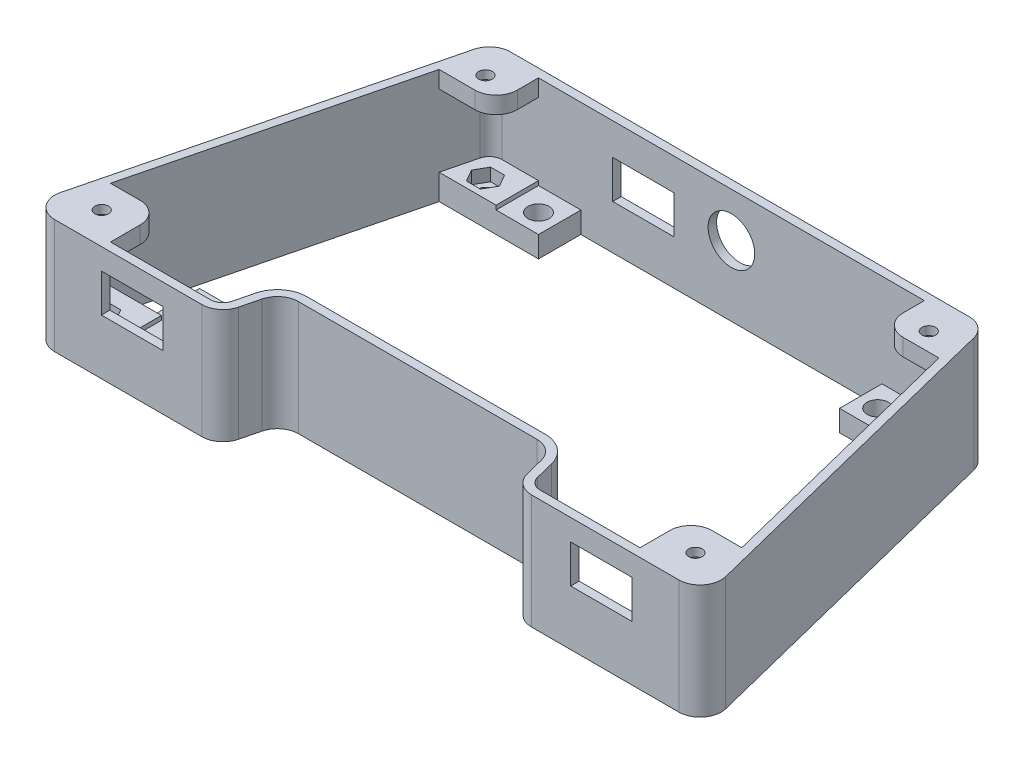
SolidWorks part; units mm, degrees
ref_plane "Ön Düzlem" through (0, 0, 0) normal (0, 0, 1) x (1, 0, 0)
ref_plane "Üst Düzlem" through (0, 0, 0) normal (0, 1, 0) x (1, 0, 0)
ref_plane "Sağ Düzlem" through (0, 0, 0) normal (1, 0, 0) x (0, 0, -1)
sketch "Çizim1" plane through (0, 0, 0) normal (0, 1, 0) x (1, 0, 0)
  line L0 (3.9039, 0) -> (112.0961, 0)
  line L1 (116.9468, -3.7873) -> (136.4468, -81.7873)
  line L2 (131.5961, -88) -> (96.9039, -88)
  line L3 (92.0532, -84.2127) -> (90.9468, -79.7873)
  line L4 (86.0961, -76) -> (29.9039, -76)
  line L5 (25.0532, -79.7873) -> (23.9468, -84.2127)
  line L6 (19.0961, -88) -> (-15.5961, -88)
  line L7 (-20.4468, -81.7873) -> (-0.9468, -3.7873)
  line L8 (58, 0) -> (58, -76) construction
  arc A0 (23.9468, -84.2127) -> (19.0961, -88) centre (19.0961, -83) cw
  arc A1 (96.9039, -88) -> (92.0532, -84.2127) centre (96.9039, -83) cw
  arc A2 (29.9039, -76) -> (25.0532, -79.7873) centre (29.9039, -81) ccw
  arc A3 (90.9468, -79.7873) -> (86.0961, -76) centre (86.0961, -81) ccw
  arc A4 (131.5961, -88) -> (136.4468, -81.7873) centre (131.5961, -83) ccw
  arc A5 (-15.5961, -88) -> (-20.4468, -81.7873) centre (-15.5961, -83) cw
  arc A6 (116.9468, -3.7873) -> (112.0961, 0) centre (112.0961, -5) ccw
  arc A7 (3.9039, 0) -> (-0.9468, -3.7873) centre (3.9039, -5) ccw
  point P18 (23, -88)
  point P21 (93, -88)
  point P28 (138, -88)
  point P31 (-22, -88)
  point P34 (116, 0)
  point P37 (0, 0)
  dimension "D6" = 5
  dimension "D7" = 5
  dimension "D1" = 116
  dimension "D2" = 160
  dimension "D3" = 76
  dimension "D4" = 12
  dimension "D5" = 45
extrude "Yükseklik-Ekstrüzyon1" add sketch "Çizim1" along normal blind 3
sketch "Çizim2" plane through (0, 3, 0) normal (0, 1, 0) x (1, 0, 0)
  line L8 (23.9468, -84.2127) -> (25.0532, -79.7873)
  line L9 (29.9039, -76) -> (86.0961, -76)
  line L10 (90.9468, -79.7873) -> (92.0532, -84.2127)
  line L11 (96.9039, -88) -> (131.5961, -88)
  line L12 (136.4468, -81.7873) -> (116.9468, -3.7873)
  line L13 (112.0961, 0) -> (3.9039, 0)
  line L14 (-0.9468, -3.7873) -> (-20.4468, -81.7873)
  line L15 (-15.5961, -88) -> (19.0961, -88)
  line L16 (23.9468, -84.2127) -> (25.0532, -79.7873)
  line L17 (29.9039, -76) -> (86.0961, -76)
  line L18 (90.9468, -79.7873) -> (92.0532, -84.2127)
  line L19 (96.9039, -88) -> (131.5961, -88)
  line L20 (136.4468, -81.7873) -> (116.9468, -3.7873)
  line L21 (112.0961, 0) -> (3.9039, 0)
  line L22 (-0.9468, -3.7873) -> (-20.4468, -81.7873)
  line L23 (-15.5961, -88) -> (19.0961, -88)
  line L32 (22.0065, -83.7276) -> (23.1129, -79.3023)
  line L33 (29.9039, -74) -> (86.0961, -74)
  line L34 (92.8871, -79.3023) -> (93.9935, -83.7276)
  line L35 (96.9039, -86) -> (131.5961, -86)
  line L36 (134.5065, -82.2724) -> (115.0065, -4.2724)
  line L37 (112.0961, -2) -> (3.9039, -2)
  line L38 (0.9935, -4.2724) -> (-18.5065, -82.2724)
  line L39 (-15.5961, -86) -> (19.0961, -86)
  line L40 (22.0065, -83.7276) -> (23.1129, -79.3023)
  line L41 (29.9039, -74) -> (86.0961, -74)
  line L42 (92.8871, -79.3023) -> (93.9935, -83.7276)
  line L43 (96.9039, -86) -> (131.5961, -86)
  line L44 (134.5065, -82.2724) -> (115.0065, -4.2724)
  line L45 (112.0961, -2) -> (3.9039, -2)
  line L46 (0.9935, -4.2724) -> (-18.5065, -82.2724)
  line L47 (-15.5961, -86) -> (19.0961, -86)
  arc A8 (19.0961, -88) -> (23.9468, -84.2127) centre (19.0961, -83) ccw
  arc A9 (29.9039, -76) -> (25.0532, -79.7873) centre (29.9039, -81) ccw
  arc A10 (90.9468, -79.7873) -> (86.0961, -76) centre (86.0961, -81) ccw
  arc A11 (92.0532, -84.2127) -> (96.9039, -88) centre (96.9039, -83) ccw
  arc A12 (131.5961, -88) -> (136.4468, -81.7873) centre (131.5961, -83) ccw
  arc A13 (116.9468, -3.7873) -> (112.0961, 0) centre (112.0961, -5) ccw
  arc A14 (3.9039, 0) -> (-0.9468, -3.7873) centre (3.9039, -5) ccw
  arc A15 (-20.4468, -81.7873) -> (-15.5961, -88) centre (-15.5961, -83) ccw
  arc A16 (19.0961, -88) -> (23.9468, -84.2127) centre (19.0961, -83) ccw
  arc A17 (29.9039, -76) -> (25.0532, -79.7873) centre (29.9039, -81) ccw
  arc A18 (90.9468, -79.7873) -> (86.0961, -76) centre (86.0961, -81) ccw
  arc A19 (92.0532, -84.2127) -> (96.9039, -88) centre (96.9039, -83) ccw
  arc A20 (131.5961, -88) -> (136.4468, -81.7873) centre (131.5961, -83) ccw
  arc A21 (116.9468, -3.7873) -> (112.0961, 0) centre (112.0961, -5) ccw
  arc A22 (3.9039, 0) -> (-0.9468, -3.7873) centre (3.9039, -5) ccw
  arc A23 (-20.4468, -81.7873) -> (-15.5961, -88) centre (-15.5961, -83) ccw
  arc A32 (19.0961, -86) -> (22.0065, -83.7276) centre (19.0961, -83) ccw
  arc A33 (29.9039, -74) -> (23.1129, -79.3023) centre (29.9039, -81) ccw
  arc A34 (92.8871, -79.3023) -> (86.0961, -74) centre (86.0961, -81) ccw
  arc A35 (93.9935, -83.7276) -> (96.9039, -86) centre (96.9039, -83) ccw
  arc A36 (131.5961, -86) -> (134.5065, -82.2724) centre (131.5961, -83) ccw
  arc A37 (115.0065, -4.2724) -> (112.0961, -2) centre (112.0961, -5) ccw
  arc A38 (3.9039, -2) -> (0.9935, -4.2724) centre (3.9039, -5) ccw
  arc A39 (-18.5065, -82.2724) -> (-15.5961, -86) centre (-15.5961, -83) ccw
  arc A40 (19.0961, -86) -> (22.0065, -83.7276) centre (19.0961, -83) ccw
  arc A41 (29.9039, -74) -> (23.1129, -79.3023) centre (29.9039, -81) ccw
  arc A42 (92.8871, -79.3023) -> (86.0961, -74) centre (86.0961, -81) ccw
  arc A43 (93.9935, -83.7276) -> (96.9039, -86) centre (96.9039, -83) ccw
  arc A44 (131.5961, -86) -> (134.5065, -82.2724) centre (131.5961, -83) ccw
  arc A45 (115.0065, -4.2724) -> (112.0961, -2) centre (112.0961, -5) ccw
  arc A46 (3.9039, -2) -> (0.9935, -4.2724) centre (3.9039, -5) ccw
  arc A47 (-18.5065, -82.2724) -> (-15.5961, -86) centre (-15.5961, -83) ccw
  dimension "D1" = 0
  dimension "D2" = 2
extrude "Yükseklik-Ekstrüzyon2" add sketch "Çizim2" along normal blind 24
sketch "Çizim3" plane through (0, 3, 0) normal (0, 1, 0) x (1, 0, 0)
  line L8 (-15.5961, -86) -> (19.0961, -86)
  line L9 (22.0065, -83.7276) -> (23.1129, -79.3023)
  line L10 (29.9039, -74) -> (86.0961, -74)
  line L11 (92.8871, -79.3023) -> (93.9935, -83.7276)
  line L12 (96.9039, -86) -> (131.5961, -86)
  line L13 (134.5065, -82.2724) -> (115.0065, -4.2724)
  line L14 (112.0961, -2) -> (3.9039, -2)
  line L15 (0.9935, -4.2724) -> (-18.5065, -82.2724)
  line L16 (-15.5961, -86) -> (19.0961, -86)
  line L17 (22.0065, -83.7276) -> (23.1129, -79.3023)
  line L18 (29.9039, -74) -> (86.0961, -74)
  line L19 (92.8871, -79.3023) -> (93.9935, -83.7276)
  line L20 (96.9039, -86) -> (131.5961, -86)
  line L21 (134.5065, -82.2724) -> (115.0065, -4.2724)
  line L22 (112.0961, -2) -> (3.9039, -2)
  line L23 (0.9935, -4.2724) -> (-18.5065, -82.2724)
  arc A8 (19.0961, -86) -> (22.0065, -83.7276) centre (19.0961, -83) ccw
  arc A9 (29.9039, -74) -> (23.1129, -79.3023) centre (29.9039, -81) ccw
  arc A10 (92.8871, -79.3023) -> (86.0961, -74) centre (86.0961, -81) ccw
  arc A11 (93.9935, -83.7276) -> (96.9039, -86) centre (96.9039, -83) ccw
  arc A12 (131.5961, -86) -> (134.5065, -82.2724) centre (131.5961, -83) ccw
  arc A13 (115.0065, -4.2724) -> (112.0961, -2) centre (112.0961, -5) ccw
  arc A14 (3.9039, -2) -> (0.9935, -4.2724) centre (3.9039, -5) ccw
  arc A15 (-18.5065, -82.2724) -> (-15.5961, -86) centre (-15.5961, -83) ccw
  arc A16 (19.0961, -86) -> (22.0065, -83.7276) centre (19.0961, -83) ccw
  arc A17 (29.9039, -74) -> (23.1129, -79.3023) centre (29.9039, -81) ccw
  arc A18 (92.8871, -79.3023) -> (86.0961, -74) centre (86.0961, -81) ccw
  arc A19 (93.9935, -83.7276) -> (96.9039, -86) centre (96.9039, -83) ccw
  arc A20 (131.5961, -86) -> (134.5065, -82.2724) centre (131.5961, -83) ccw
  arc A21 (115.0065, -4.2724) -> (112.0961, -2) centre (112.0961, -5) ccw
  arc A22 (3.9039, -2) -> (0.9935, -4.2724) centre (3.9039, -5) ccw
  arc A23 (-18.5065, -82.2724) -> (-15.5961, -86) centre (-15.5961, -83) ccw
  dimension "D1" = 0
extrude "Kes-Ekstrüzyon1" cut sketch "Çizim3" against normal blind 27
sketch "Çizim4" plane through (0, 0, 0) normal (0, 0, -1) x (-1, 0, 0)
  line L0 (-3.9039, 16.5) -> (-112.0961, 16.5) construction
  line L1 (-3.9039, 27) -> (-3.9039, 0) construction
  line L2 (-112.0961, 27) -> (-112.0961, 0) construction
  line L3 (-112.0961, 0) -> (-3.9039, 0) construction
  line L4 (-58, 16.5) -> (-58, 0) construction
  circle A0 centre (-58, 16.5) radius 5.5
  dimension "D2" = 11
  dimension "D1" = 16.5
extrude "Kes-Ekstrüzyon2" cut sketch "Çizim4" against normal blind 10
sketch "Çizim5" plane through (0, 0, 0) normal (0, 0, -1) x (-1, 0, 0)
  line L0 (-3.9039, 15) -> (-112.0961, 15) construction
  line L1 (-3.9039, 27) -> (-3.9039, 0) construction
  line L2 (-112.0961, 27) -> (-112.0961, 0) construction
  line L3 (-112.0961, 0) -> (-3.9039, 0) construction
  line L4 (-30, 10.5) -> (-44.5, 10.5)
  line L5 (-30, 10.5) -> (-30, 19.5)
  line L6 (-30, 19.5) -> (-44.5, 19.5)
  line L7 (-44.5, 10.5) -> (-44.5, 19.5)
  dimension "D1" = 14.5
  dimension "D2" = 9
  dimension "D3" = 30
  dimension "D4" = 15
extrude "Kes-Ekstrüzyon3" cut sketch "Çizim5" against normal blind 10
sketch "Çizim7" plane through (0, 0, 0) normal (0, -1, 0) x (1, 0, 0)
  line L0 (10.5616, 2) -> (10.5616, 10)
  line L1 (3.9039, 2) -> (112.0961, 2) construction
  line L2 (6.5616, 14) -> (-1.4384, 14)
  line L3 (-18.5065, 82.2724) -> (0.9935, 4.2724) construction
  line L4 (-1.4384, 14) -> (0.9935, 4.2724)
  line L5 (3.9039, 2) -> (10.5616, 2)
  line L6 (58, 2) -> (58, 74) construction
  line L7 (86.0961, 74) -> (29.9039, 74) construction
  line L8 (112.0961, 2) -> (105.4384, 2)
  line L9 (117.4384, 14) -> (115.0065, 4.2724)
  line L10 (109.4384, 14) -> (117.4384, 14)
  line L11 (105.4384, 2) -> (105.4384, 10)
  line L12 (113.9424, 2.6354) -> (106.61, 12.8284) construction
  line L13 (2.0576, 2.6354) -> (9.39, 12.8284) construction
  arc A0 (0.9935, 4.2724) -> (3.9039, 2) centre (3.9039, 5) ccw construction
  arc A1 (0.9935, 4.2724) -> (3.9039, 2) centre (3.9039, 5) ccw
  arc A2 (6.5616, 14) -> (10.5616, 10) centre (6.5616, 10) cw
  arc A3 (109.4384, 14) -> (105.4384, 10) centre (109.4384, 10) ccw
  arc A4 (115.0065, 4.2724) -> (112.0961, 2) centre (112.0961, 5) cw
  circle A5 centre (110.2762, 7.7319) radius 1.65
  circle A6 centre (5.7238, 7.7319) radius 1.65
  point P10 (10.5616, 14)
  point P22 (105.4384, 14)
  dimension "D3" = 4
  dimension "D4" = 3.3
  dimension "D5" = 3.3
  dimension "D1" = 12
  dimension "D2" = 12
extrude "Yükseklik-Ekstrüzyon3" add sketch "Çizim7" against normal blind 2
sketch "Çizim8" plane through (0, 0, 0) normal (0, -1, 0) x (1, 0, 0)
  line L0 (132.4384, 74) -> (124.4384, 74)
  line L1 (117.4384, 14) -> (134.5065, 82.2724) construction
  line L2 (120.4384, 78) -> (120.4384, 86)
  line L3 (131.5961, 86) -> (96.9039, 86) construction
  line L4 (131.5961, 86) -> (120.4384, 86)
  line L5 (132.4384, 74) -> (134.5065, 82.2724)
  line L6 (58, 74) -> (58, 39.038) construction
  line L7 (-16.4384, 74) -> (-18.5065, 82.2724)
  line L8 (124.4384, 78) -> (131.5961, 83) construction
  line L9 (-15.5961, 86) -> (-4.4384, 86)
  line L10 (-4.4384, 78) -> (-4.4384, 86)
  line L11 (-16.4384, 74) -> (-8.4384, 74)
  line L13 (29.9039, 74) -> (86.0961, 74) construction
  arc A0 (134.5065, 82.2724) -> (131.5961, 86) centre (131.5961, 83) ccw construction
  arc A1 (134.5065, 82.2724) -> (131.5961, 86) centre (131.5961, 83) ccw
  arc A2 (120.4384, 78) -> (124.4384, 74) centre (124.4384, 78) ccw
  circle A3 centre (128.0173, 80.5) radius 1.65
  circle A4 centre (-12.0173, 80.5) radius 1.65
  arc A5 (-4.4384, 78) -> (-8.4384, 74) centre (-8.4384, 78) cw
  arc A6 (-18.5065, 82.2724) -> (-15.5961, 86) centre (-15.5961, 83) cw
  point P10 (120.4384, 74)
  point P27 (-4.4384, 74)
  dimension "D3" = 4
  dimension "D4" = 3.3
  dimension "D1" = 12
  dimension "D2" = 12
extrude "Yükseklik-Ekstrüzyon4" add sketch "Çizim8" against normal blind 2
sketch "Çizim12" plane through (0, 2, 0) normal (0, 1, 0) x (1, 0, 0)
  line L0 (112.0961, 0) -> (3.9039, 0) construction
  line L1 (7.4559, -4.7319) -> (3.9918, -4.7319)
  line L2 (3.9918, -4.7319) -> (2.2597, -7.7319)
  line L3 (2.2597, -7.7319) -> (3.9918, -10.7319)
  line L4 (3.9918, -10.7319) -> (7.4559, -10.7319)
  line L5 (7.4559, -10.7319) -> (9.1879, -7.7319)
  line L6 (9.1879, -7.7319) -> (7.4559, -4.7319)
  line L7 (-15.5961, -88) -> (19.0961, -88) construction
  line L8 (-8.5532, -80.5) -> (-10.2852, -77.5)
  line L9 (-10.2852, -77.5) -> (-13.7493, -77.5)
  line L10 (-13.7493, -77.5) -> (-15.4814, -80.5)
  line L11 (-15.4814, -80.5) -> (-13.7493, -83.5)
  line L12 (-13.7493, -83.5) -> (-10.2852, -83.5)
  line L13 (-10.2852, -83.5) -> (-8.5532, -80.5)
  line L14 (58, -2) -> (58, -74) construction
  line L15 (112.0961, -2) -> (3.9039, -2) construction
  line L16 (29.9039, -74) -> (86.0961, -74) construction
  line L17 (126.2852, -83.5) -> (124.5532, -80.5)
  line L18 (129.7493, -83.5) -> (126.2852, -83.5)
  line L19 (131.4814, -80.5) -> (129.7493, -83.5)
  line L20 (129.7493, -77.5) -> (131.4814, -80.5)
  line L21 (126.2852, -77.5) -> (129.7493, -77.5)
  line L22 (124.5532, -80.5) -> (126.2852, -77.5)
  line L23 (106.8121, -7.7319) -> (108.5441, -4.7319)
  line L24 (108.5441, -10.7319) -> (106.8121, -7.7319)
  line L25 (112.0082, -10.7319) -> (108.5441, -10.7319)
  line L26 (113.7403, -7.7319) -> (112.0082, -10.7319)
  line L27 (112.0082, -4.7319) -> (113.7403, -7.7319)
  line L28 (108.5441, -4.7319) -> (112.0082, -4.7319)
  circle A0 centre (5.7238, -7.7319) radius 3 construction
  circle A1 centre (-12.0173, -80.5) radius 3 construction
  circle A2 centre (128.0173, -80.5) radius 3 construction
  circle A3 centre (110.2762, -7.7319) radius 3 construction
  dimension "D1" = 6
  dimension "D2" = 6
extrude "Kes-Ekstrüzyon5" cut sketch "Çizim12" against normal blind 10
sketch "Çizim13" plane through (0, 0, 88) normal (0, 0, 1) x (1, 0, 0)
  line L0 (-15.5961, 17.5) -> (136.5961, 17.5) construction
  line L1 (-15.5961, 27) -> (-15.5961, 0) construction
  line L2 (136.5961, 0) -> (136.5961, 27) construction
  line L3 (60.5, 17.5) -> (60.5, 0) construction
  line L4 (-4.5961, 22) -> (9.9039, 22)
  line L5 (-4.5961, 22) -> (-4.5961, 13)
  line L6 (-4.5961, 13) -> (9.9039, 13)
  line L7 (9.9039, 22) -> (9.9039, 13)
  line L8 (29.9039, 0) -> (86.0961, 0) construction
  line L9 (106.0939, 22) -> (106.0939, 13)
  line L10 (120.5939, 13) -> (106.0939, 13)
  line L11 (120.5939, 22) -> (120.5939, 13)
  line L12 (120.5939, 22) -> (106.0939, 22)
  line L13 (96.9039, 27) -> (96.9039, 0) construction
  point P25 (96.9039, 13.5)
  dimension "D1" = 9
  dimension "D2" = 14.5
  dimension "D3" = 5
  dimension "D4" = 11
  dimension "D5" = 14.5
  dimension "D6" = 9
  dimension "D7" = 9.19
extrude "Kes-Ekstrüzyon6" cut sketch "Çizim13" against normal blind 10
sketch "Çizim14" plane through (0, 2, 0) normal (0, 1, 0) x (1, 0, 0)
  line L0 (10.5616, -6) -> (105.4384, -6) construction
  line L1 (10.5616, -2) -> (10.5616, -10) construction
  line L2 (105.4384, -10) -> (105.4384, -2) construction
  line L3 (6.5616, -14) -> (12.5, -14)
  line L4 (12.5, -14) -> (12.5, -2)
  line L5 (112.0961, -2) -> (3.9039, -2) construction
  line L6 (12.5, -2) -> (10.5616, -2)
  line L7 (10.5616, -2) -> (3.9039, -2)
  line L8 (0.9935, -4.2724) -> (-1.4384, -14)
  line L9 (-1.4384, -14) -> (6.5616, -14)
  line L10 (10.5616, -10) -> (10.5616, -2)
  line L14 (10.5616, -10) -> (10.5616, -2)
  line L15 (109.4384, -14) -> (103.5, -14)
  line L16 (103.5, -14) -> (103.5, -2)
  line L17 (103.5, -2) -> (105.4384, -2)
  line L18 (58, -6) -> (58, -2) construction
  line L22 (112.0961, -2) -> (105.4384, -2)
  line L23 (105.4384, -2) -> (105.4384, -10)
  line L24 (109.4384, -14) -> (117.4384, -14)
  line L25 (117.4384, -14) -> (115.0065, -4.2724)
  line L27 (105.4384, -2) -> (105.4384, -10)
  arc A2 (3.9039, -2) -> (0.9935, -4.2724) centre (3.9039, -5) ccw
  arc A3 (6.5616, -14) -> (10.5616, -10) centre (6.5616, -10) ccw
  arc A5 (6.5616, -14) -> (10.5616, -10) centre (6.5616, -10) ccw
  arc A6 (115.0065, -4.2724) -> (112.0961, -2) centre (112.0961, -5) ccw
  arc A7 (105.4384, -10) -> (109.4384, -14) centre (109.4384, -10) ccw
  arc A9 (105.4384, -10) -> (109.4384, -14) centre (109.4384, -10) ccw
  dimension "D3" = 91
  dimension "D1" = 0
  dimension "D2" = 0
extrude "Yükseklik-Ekstrüzyon5" add sketch "Çizim14" against normal up to vertex (2 mm away)
sketch "Çizim15" plane through (0, 2, 0) normal (0, 1, 0) x (1, 0, 0)
  line L0 (12.5, -7.5) -> (103.5, -7.5) construction
  line L1 (12.5, -14) -> (12.5, -2) construction
  line L2 (103.5, -2) -> (103.5, -14) construction
  line L3 (112.0961, -2) -> (3.9039, -2) construction
  line L4 (58, -7.5) -> (58, -24.859) construction
  line L6 (12.5, -14) -> (22.5, -14)
  line L7 (12.5, -14) -> (12.5, -2)
  line L8 (12.5, -2) -> (22.5, -2)
  line L9 (22.5, -14) -> (22.5, -2)
  line L10 (93.5, -2) -> (103.5, -2)
  line L11 (93.5, -2) -> (93.5, -14)
  line L12 (93.5, -14) -> (103.5, -14)
  line L13 (103.5, -2) -> (103.5, -14)
  circle A0 centre (18, -7.5) radius 1.6
  circle A1 centre (98, -7.5) radius 1.6
  dimension "D2" = 3.2
  dimension "D3" = 80
  dimension "D1" = 5.5
  dimension "D4" = 10
extrude "Yükseklik-Ekstrüzyon6" add sketch "Çizim15" along normal blind 3 and the other way blind 2
sketch "Çizim16" plane through (0, 2, 0) normal (0, 1, 0) x (1, 0, 0)
  line L4 (12.5, -2) -> (3.9039, -2)
  line L5 (0.9935, -4.2724) -> (-1.4384, -14)
  line L6 (-1.4384, -14) -> (12.5, -14)
  line L7 (12.5, -14) -> (12.5, -2)
  line L8 (12.5, -2) -> (3.9039, -2)
  line L9 (0.9935, -4.2724) -> (-1.4384, -14)
  line L10 (-1.4384, -14) -> (12.5, -14)
  line L11 (12.5, -14) -> (12.5, -2)
  line L12 (112.0961, -2) -> (103.5, -2)
  line L13 (103.5, -2) -> (103.5, -14)
  line L14 (103.5, -14) -> (117.4384, -14)
  line L15 (117.4384, -14) -> (115.0065, -4.2724)
  line L16 (112.0961, -2) -> (103.5, -2)
  line L17 (103.5, -2) -> (103.5, -14)
  line L18 (103.5, -14) -> (117.4384, -14)
  line L19 (117.4384, -14) -> (115.0065, -4.2724)
  arc A1 (3.9039, -2) -> (0.9935, -4.2724) centre (3.9039, -5) ccw
  arc A2 (3.9039, -2) -> (0.9935, -4.2724) centre (3.9039, -5) ccw
  arc A3 (115.0065, -4.2724) -> (112.0961, -2) centre (112.0961, -5) ccw
  arc A4 (115.0065, -4.2724) -> (112.0961, -2) centre (112.0961, -5) ccw
  dimension "D1" = 0
  dimension "D2" = 0
extrude "Yükseklik-Ekstrüzyon7" add sketch "Çizim16" along normal blind 4
sketch "Çizim17" plane through (0, 0, 0) normal (0, -1, 0) x (1, 0, 0)
  line L0 (112.0082, 4.7319) -> (113.7403, 7.7319) construction
  line L1 (112.0082, 4.7319) -> (113.7403, 7.7319)
  line L2 (113.7403, 7.7319) -> (112.0082, 10.7319)
  line L3 (112.0082, 10.7319) -> (108.5441, 10.7319)
  line L4 (108.5441, 10.7319) -> (106.8121, 7.7319)
  line L5 (106.8121, 7.7319) -> (108.5441, 4.7319)
  line L6 (108.5441, 4.7319) -> (112.0082, 4.7319)
  line L7 (108.5441, 4.7319) -> (112.0082, 4.7319) construction
  line L8 (112.0082, 10.7319) -> (108.5441, 10.7319) construction
  line L9 (3.9918, 4.7319) -> (7.4559, 4.7319) construction
  line L10 (7.4559, 4.7319) -> (9.1879, 7.7319)
  line L11 (9.1879, 7.7319) -> (7.4559, 10.7319)
  line L12 (7.4559, 10.7319) -> (3.9918, 10.7319)
  line L13 (3.9918, 10.7319) -> (2.2597, 7.7319)
  line L14 (2.2597, 7.7319) -> (3.9918, 4.7319)
  line L15 (3.9918, 4.7319) -> (7.4559, 4.7319)
  line L16 (9.1879, 7.7319) -> (7.4559, 4.7319) construction
  circle A0 centre (110.2762, 7.7319) radius 3 construction
  circle A1 centre (110.2762, 7.7319) radius 1.6
  circle A2 centre (5.7238, 7.7319) radius 1.6
  circle A3 centre (5.7238, 7.7319) radius 3 construction
  dimension "D1" = 3.2
  dimension "D2" = 6
  dimension "D3" = 3.2
extrude "Yükseklik-Ekstrüzyon8" add sketch "Çizim17" against normal blind 3
sketch "Çizim18" plane through (0, 2, 0) normal (0, -1, 0) x (1, 0, 0)
  circle A1 centre (110.2762, 7.7319) radius 1.6
  circle A2 centre (110.2762, 7.7319) radius 1.6
  circle A3 centre (5.7238, 7.7319) radius 1.6
  circle A4 centre (5.7238, 7.7319) radius 1.6
  dimension "D1" = 0
  dimension "D2" = 0
extrude "Kes-Ekstrüzyon7" cut sketch "Çizim18" against normal blind 3
sketch "Çizim19" plane through (0, 6, 0) normal (0, 1, 0) x (1, 0, 0)
  line L0 (-1.4384, -14) -> (12.5, -14) construction
  line L1 (7.3693, -4.8819) -> (4.0784, -4.8819)
  line L2 (4.0784, -4.8819) -> (2.4329, -7.7319)
  line L3 (2.4329, -7.7319) -> (4.0784, -10.5819)
  line L4 (4.0784, -10.5819) -> (7.3693, -10.5819)
  line L5 (7.3693, -10.5819) -> (9.0147, -7.7319)
  line L6 (9.0147, -7.7319) -> (7.3693, -4.8819)
  line L7 (103.5, -14) -> (117.4384, -14) construction
  line L8 (106.9853, -7.7319) -> (108.6307, -10.5819)
  line L9 (108.6307, -10.5819) -> (111.9216, -10.5819)
  line L10 (111.9216, -10.5819) -> (113.5671, -7.7319)
  line L11 (113.5671, -7.7319) -> (111.9216, -4.8819)
  line L12 (111.9216, -4.8819) -> (108.6307, -4.8819)
  line L13 (108.6307, -4.8819) -> (106.9853, -7.7319)
  circle A0 centre (5.7238, -7.7319) radius 2.85 construction
  circle A1 centre (110.2762, -7.7319) radius 2.85 construction
  dimension "D1" = 5.7
  dimension "D2" = 5.7
extrude "Kes-Ekstrüzyon8" cut sketch "Çizim19" against normal blind 3
sketch "Çizim20" plane through (0, 6, 0) normal (0, 1, 0) x (1, 0, 0)
  line L0 (0.9935, -4.2724) -> (-1.4384, -14) construction
  line L1 (-1.4384, -14) -> (117.4384, -14)
  line L3 (-0.9384, -12) -> (116.9384, -12)
  line L5 (-0.9384, -12) -> (-1.4384, -14)
  line L6 (134.5065, -82.2724) -> (115.0065, -4.2724) construction
  line L7 (134.5065, -82.2724) -> (116.9384, -12)
  line M9 (12.5, -14) -> (12.5, -2)
  line M12 (0.9935, -4.2724) -> (-1.4384, -14)
  line M13 (-1.4384, -14) -> (12.5, -14)
  dimension "D1" = 2
extrude "Kes-Ekstrüzyon9" cut sketch "Çizim20" against normal blind 10 contours L3 M12 M13 M9 | L1 L7 L3 M9
sketch "Çizim21" plane through (0, 5, 0) normal (0, 1, 0) x (1, 0, 0)
  circle A0 centre (18, -7.5) radius 2.5
  circle A1 centre (98, -7.5) radius 2.5
  dimension "D1" = 5
  dimension "D2" = 5
extrude "Kes-Ekstrüzyon10" cut sketch "Çizim21" against normal blind 10
sketch "Çizim22" plane through (0, 2, 0) normal (0, 1, 0) x (1, 0, 0)
  line L0 (-15.5961, -86) -> (19.0961, -86) construction
  line L1 (5.5616, -86) -> (-4.4384, -86)
  line L2 (5.5616, -86) -> (5.5616, -66)
  line L3 (5.5616, -66) -> (-4.4384, -66)
  line L4 (-4.4384, -86) -> (-4.4384, -78)
  line L5 (-4.4384, -78) -> (-4.4384, -86) construction
  line L6 (-8.4384, -74) -> (-4.4384, -74)
  line L7 (-4.4384, -74) -> (-4.4384, -66)
  line L8 (-16.4384, -74) -> (-8.4384, -74) construction
  line L9 (96.9039, -86) -> (131.5961, -86) construction
  line L10 (110.4384, -86) -> (120.4384, -86)
  line L11 (110.4384, -86) -> (110.4384, -66)
  line L12 (110.4384, -66) -> (120.4384, -66)
  line L13 (120.4384, -86) -> (120.4384, -78)
  line L14 (120.4384, -86) -> (120.4384, -78) construction
  line L15 (124.4384, -74) -> (120.4384, -74)
  line L16 (120.4384, -74) -> (120.4384, -66)
  arc A0 (-4.4384, -78) -> (-8.4384, -74) centre (-8.4384, -78) ccw construction
  arc A1 (-4.4384, -78) -> (-8.4384, -74) centre (-8.4384, -78) ccw
  arc A2 (124.4384, -74) -> (120.4384, -78) centre (124.4384, -78) ccw construction
  arc A3 (124.4384, -74) -> (120.4384, -78) centre (124.4384, -78) ccw
  dimension "D1" = 20
  dimension "D2" = 10
  dimension "D3" = 10
  dimension "D4" = 20
extrude "Yükseklik-Ekstrüzyon9" add sketch "Çizim22" against normal up to vertex (2 mm away)
sketch "Çizim23" plane through (0, 2, 0) normal (0, 1, 0) x (1, 0, 0)
  line L0 (120.4384, -74) -> (120.4384, -86)
  line L1 (-4.4384, -74) -> (-4.4384, -86)
  line L6 (132.4384, -74) -> (120.4384, -74)
  line L7 (120.4384, -74) -> (120.4384, -66)
  line L8 (120.4384, -66) -> (110.4384, -66)
  line L9 (110.4384, -66) -> (110.4384, -86)
  line L10 (110.4384, -86) -> (131.5961, -86)
  line L11 (134.5065, -82.2724) -> (132.4384, -74)
  line L12 (132.4384, -74) -> (120.4384, -74)
  line L14 (-15.5961, -86) -> (5.5616, -86)
  line L15 (5.5616, -86) -> (5.5616, -66)
  line L16 (120.4384, -86) -> (131.5961, -86)
  line L17 (134.5065, -82.2724) -> (132.4384, -74)
  line L18 (5.5616, -66) -> (-4.4384, -66)
  line L19 (-4.4384, -66) -> (-4.4384, -74)
  line L20 (-4.4384, -74) -> (-16.4384, -74)
  line L21 (-16.4384, -74) -> (-18.5065, -82.2724)
  line L22 (-15.5961, -86) -> (-4.4384, -86)
  line L25 (-4.4384, -66) -> (-4.4384, -74)
  line L26 (-4.4384, -74) -> (-16.4384, -74)
  line L27 (-16.4384, -74) -> (-18.5065, -82.2724)
  arc A1 (131.5961, -86) -> (134.5065, -82.2724) centre (131.5961, -83) ccw
  arc A2 (131.5961, -86) -> (134.5065, -82.2724) centre (131.5961, -83) ccw
  arc A3 (-18.5065, -82.2724) -> (-15.5961, -86) centre (-15.5961, -83) ccw
  arc A4 (-18.5065, -82.2724) -> (-15.5961, -86) centre (-15.5961, -83) ccw
  line M15 (132.4384, -74) -> (120.4384, -74)
  line M19 (110.4384, -86) -> (131.5961, -86)
  arc M20 (131.5961, -86) -> (134.5065, -82.2724) centre (131.5961, -83) ccw
  line M21 (134.5065, -82.2724) -> (132.4384, -74)
  line M22 (131.4814, -80.5) -> (129.7493, -83.5)
  line M23 (129.7493, -83.5) -> (126.2852, -83.5)
  line M24 (126.2852, -83.5) -> (124.5532, -80.5)
  line M25 (124.5532, -80.5) -> (126.2852, -77.5)
  line M26 (126.2852, -77.5) -> (129.7493, -77.5)
  line M27 (129.7493, -77.5) -> (131.4814, -80.5)
  dimension "D1" = 0
  dimension "D2" = 0
extrude "Yükseklik-Ekstrüzyon10" add sketch "Çizim23" along normal blind 4 contours L27 A4 L22 L1 L26 | L0 M15 M19 M20 M21 M27 M22 M23 M24 M25 M26 | M22 M27 M26 M25 M24 M23
sketch "Çizim24" plane through (0, 2, 0) normal (0, -1, 0) x (1, 0, 0)
  line L0 (126.2852, 77.5) -> (129.7493, 77.5) construction
  line L1 (129.7493, 77.5) -> (131.4814, 80.5)
  line L2 (131.4814, 80.5) -> (129.7493, 83.5)
  line L3 (129.7493, 83.5) -> (126.2852, 83.5)
  line L4 (126.2852, 83.5) -> (124.5532, 80.5)
  line L5 (124.5532, 80.5) -> (126.2852, 77.5)
  line L6 (126.2852, 77.5) -> (129.7493, 77.5)
  line L7 (129.7493, 77.5) -> (131.4814, 80.5) construction
  line L8 (124.5532, 80.5) -> (126.2852, 83.5) construction
  line L9 (-10.2852, 77.5) -> (-13.7493, 77.5) construction
  line L10 (-10.2852, 77.5) -> (-8.5532, 80.5)
  line L11 (-8.5532, 80.5) -> (-10.2852, 83.5)
  line L12 (-10.2852, 83.5) -> (-13.7493, 83.5)
  line L13 (-13.7493, 83.5) -> (-15.4814, 80.5)
  line L14 (-15.4814, 80.5) -> (-13.7493, 77.5)
  line L15 (-13.7493, 77.5) -> (-10.2852, 77.5)
  line L16 (-10.2852, 77.5) -> (-8.5532, 80.5) construction
  line L17 (-15.4814, 80.5) -> (-13.7493, 83.5) construction
  circle A0 centre (128.0173, 80.5) radius 3 construction
  circle A1 centre (128.0173, 80.5) radius 1.6
  circle A2 centre (-12.0173, 80.5) radius 1.6
  circle A3 centre (-12.0173, 80.5) radius 3 construction
  dimension "D1" = 3.2
  dimension "D2" = 3.2
extrude "Yükseklik-Ekstrüzyon11" add sketch "Çizim24" along normal blind 2
sketch "Çizim25" plane through (0, 2, 0) normal (0, -1, 0) x (1, 0, 0)
  circle A1 centre (128.0173, 80.5) radius 1.6
  circle A2 centre (128.0173, 80.5) radius 1.6
  circle A3 centre (-12.0173, 80.5) radius 1.6
  circle A4 centre (-12.0173, 80.5) radius 1.6
  dimension "D1" = 0
  dimension "D2" = 0
extrude "Kes-Ekstrüzyon12" cut sketch "Çizim25" against normal blind 10
sketch "Çizim26" plane through (0, 6, 0) normal (0, 1, 0) x (1, 0, 0)
  line L0 (-15.5961, -86) -> (-4.4384, -86) construction
  line L1 (-10.3718, -77.65) -> (-13.6627, -77.65)
  line L2 (-13.6627, -77.65) -> (-15.3082, -80.5)
  line L3 (-15.3082, -80.5) -> (-13.6627, -83.35)
  line L4 (-13.6627, -83.35) -> (-10.3718, -83.35)
  line L5 (-10.3718, -83.35) -> (-8.7264, -80.5)
  line L6 (-8.7264, -80.5) -> (-10.3718, -77.65)
  line L7 (132.4384, -74) -> (120.4384, -74) construction
  line L8 (129.6627, -77.65) -> (126.3718, -77.65)
  line L9 (126.3718, -77.65) -> (124.7264, -80.5)
  line L10 (124.7264, -80.5) -> (126.3718, -83.35)
  line L11 (126.3718, -83.35) -> (129.6627, -83.35)
  line L12 (129.6627, -83.35) -> (131.3082, -80.5)
  line L13 (131.3082, -80.5) -> (129.6627, -77.65)
  circle A0 centre (-12.0173, -80.5) radius 2.85 construction
  circle A1 centre (128.0173, -80.5) radius 2.85 construction
  dimension "D1" = 5.7
  dimension "D2" = 5.7
extrude "Kes-Ekstrüzyon13" cut sketch "Çizim26" against normal up to vertex (3 mm away)
sketch "Çizim27" plane through (0, 2, 0) normal (0, 1, 0) x (1, 0, 0)
  line L5 (-4.4384, -74) -> (-4.4384, -86)
  line L6 (-4.4384, -86) -> (5.5616, -86)
  line L7 (5.5616, -86) -> (5.5616, -66)
  line L8 (5.5616, -66) -> (-4.4384, -66)
  line L9 (-4.4384, -66) -> (-4.4384, -74)
  line L10 (-4.4384, -74) -> (-4.4384, -86)
  line L11 (-4.4384, -86) -> (5.5616, -86)
  line L12 (5.5616, -86) -> (5.5616, -66)
  line L13 (5.5616, -66) -> (-4.4384, -66)
  line L14 (-4.4384, -66) -> (-4.4384, -74)
  line L15 (120.4384, -86) -> (120.4384, -74)
  line L16 (120.4384, -74) -> (120.4384, -66)
  line L17 (120.4384, -66) -> (110.4384, -66)
  line L18 (110.4384, -66) -> (110.4384, -86)
  line L19 (110.4384, -86) -> (120.4384, -86)
  line L20 (120.4384, -86) -> (120.4384, -74)
  line L21 (120.4384, -74) -> (120.4384, -66)
  line L22 (120.4384, -66) -> (110.4384, -66)
  line L23 (110.4384, -66) -> (110.4384, -86)
  line L24 (110.4384, -86) -> (120.4384, -86)
  dimension "D1" = 0
  dimension "D2" = 0
extrude "Yükseklik-Ekstrüzyon12" add sketch "Çizim27" along normal blind 3
sketch "Çizim28" plane through (0, 5, 0) normal (0, 1, 0) x (1, 0, 0)
  line L0 (-4.4384, -74) -> (-16.4384, -74) construction
  line L1 (-4.4384, -66) -> (-6.4384, -66)
  line L2 (-4.4384, -66) -> (-4.4384, -74)
  line L3 (-4.4384, -74) -> (-6.4384, -74)
  line L4 (-6.4384, -66) -> (-6.4384, -74)
  line L5 (132.4384, -74) -> (120.4384, -74) construction
  line L6 (120.4384, -66) -> (122.4384, -66)
  line L7 (120.4384, -66) -> (120.4384, -74)
  line L8 (120.4384, -74) -> (122.4384, -74)
  line L9 (122.4384, -66) -> (122.4384, -74)
  dimension "D1" = 2
  dimension "D2" = 2
extrude "Yükseklik-Ekstrüzyon13" add sketch "Çizim28" against normal up to vertex (5 mm away)
sketch "Çizim29" plane through (0, 5, 0) normal (0, 1, 0) x (1, 0, 0)
  line L0 (-6.4384, -66) -> (-6.4384, -74) construction
  line L1 (-6.4384, -74) -> (-4.4384, -74) construction
  line L2 (132.4384, -74) -> (120.4384, -74) construction
  line L3 (122.4384, -74) -> (122.4384, -66) construction
  circle A0 centre (-1.9984, -67.5) radius 2.5
  circle A2 centre (117.9984, -67.5) radius 2.5
  point P10 (126.4384, -74)
  dimension "D1" = 5
  dimension "D2" = 4.44
  dimension "D4" = 5
  dimension "D5" = 6.5
  dimension "D3" = 6.5
  dimension "D6" = 4.44
extrude "Kes-Ekstrüzyon14" cut sketch "Çizim29" against normal blind 10
sketch "Çizim30" plane through (0, 5, 0) normal (0, 1, 0) x (1, 0, 0)
  line L0 (122.4384, -74) -> (122.4384, -66) construction
  line L1 (110.4384, -66) -> (115.9984, -66)
  line L2 (110.4384, -66) -> (110.4384, -63)
  line L3 (110.4384, -63) -> (122.4384, -63)
  line L4 (122.4384, -66) -> (122.4384, -63)
  line L5 (119.9984, -66) -> (122.4384, -66)
  line L6 (5.5616, -86) -> (5.5616, -66) construction
  line L7 (-6.4384, -66) -> (-3.9984, -66)
  line L8 (-6.4384, -66) -> (-6.4384, -63)
  line L9 (-6.4384, -63) -> (5.5616, -63)
  line L10 (5.5616, -66) -> (5.5616, -63)
  line L11 (0.0016, -66) -> (5.5616, -66)
  arc A1 (119.9984, -66) -> (115.9984, -66) centre (117.9984, -67.5) ccw
  arc A2 (115.9984, -66) -> (119.9984, -66) centre (117.9984, -67.5) ccw construction
  arc A3 (0.0016, -66) -> (-3.9984, -66) centre (-1.9984, -67.5) ccw
  arc A4 (-3.9984, -66) -> (0.0016, -66) centre (-1.9984, -67.5) ccw construction
  dimension "D1" = 3
  dimension "D2" = 3
extrude "Yükseklik-Ekstrüzyon14" add sketch "Çizim30" against normal up to vertex (5 mm away)
sketch "Çizim31" plane through (0, 27, 0) normal (0, 1, 0) x (1, 0, 0)
  line L4 (0.9935, -4.2724) -> (-0.9384, -12)
  line L5 (-0.9384, -12) -> (12.5, -12)
  line L6 (12.5, -12) -> (12.5, -2)
  line L7 (12.5, -2) -> (3.9039, -2)
  line L8 (0.9935, -4.2724) -> (-0.9384, -12)
  line L9 (-0.9384, -12) -> (12.5, -12)
  line L10 (12.5, -12) -> (12.5, -2)
  line L11 (12.5, -2) -> (3.9039, -2)
  line L12 (103.5, -2) -> (103.5, -12)
  line L13 (103.5, -12) -> (116.9384, -12)
  line L14 (116.9384, -12) -> (115.0065, -4.2724)
  line L15 (112.0961, -2) -> (103.5, -2)
  line L16 (103.5, -2) -> (103.5, -12)
  line L17 (103.5, -12) -> (116.9384, -12)
  line L18 (116.9384, -12) -> (115.0065, -4.2724)
  line L19 (112.0961, -2) -> (103.5, -2)
  line L20 (132.4384, -74) -> (120.4384, -74)
  line L21 (120.4384, -74) -> (120.4384, -86)
  line L22 (120.4384, -86) -> (131.5961, -86)
  line L23 (134.5065, -82.2724) -> (132.4384, -74)
  line L24 (132.4384, -74) -> (120.4384, -74)
  line L25 (120.4384, -74) -> (120.4384, -86)
  line L26 (120.4384, -86) -> (131.5961, -86)
  line L27 (134.5065, -82.2724) -> (132.4384, -74)
  line L28 (-16.4384, -74) -> (-18.5065, -82.2724)
  line L29 (-15.5961, -86) -> (-4.4384, -86)
  line L30 (-4.4384, -86) -> (-4.4384, -74)
  line L31 (-4.4384, -74) -> (-16.4384, -74)
  line L32 (-16.4384, -74) -> (-18.5065, -82.2724)
  line L33 (-15.5961, -86) -> (-4.4384, -86)
  line L34 (-4.4384, -86) -> (-4.4384, -74)
  line L35 (-4.4384, -74) -> (-16.4384, -74)
  circle A0 centre (110.2762, -7.7319) radius 1.6
  arc A1 (3.9039, -2) -> (0.9935, -4.2724) centre (3.9039, -5) ccw
  arc A2 (3.9039, -2) -> (0.9935, -4.2724) centre (3.9039, -5) ccw
  arc A3 (115.0065, -4.2724) -> (112.0961, -2) centre (112.0961, -5) ccw
  arc A4 (115.0065, -4.2724) -> (112.0961, -2) centre (112.0961, -5) ccw
  circle A5 centre (110.2762, -7.7319) radius 1.6 construction
  circle A6 centre (5.7238, -7.7319) radius 1.6 construction
  circle A7 centre (5.7238, -7.7319) radius 1.6
  circle A8 centre (128.0173, -80.5) radius 1.6 construction
  arc A9 (131.5961, -86) -> (134.5065, -82.2724) centre (131.5961, -83) ccw
  arc A10 (131.5961, -86) -> (134.5065, -82.2724) centre (131.5961, -83) ccw
  circle A11 centre (128.0173, -80.5) radius 1.6
  circle A12 centre (-12.0173, -80.5) radius 1.6 construction
  arc A13 (-18.5065, -82.2724) -> (-15.5961, -86) centre (-15.5961, -83) ccw
  arc A14 (-18.5065, -82.2724) -> (-15.5961, -86) centre (-15.5961, -83) ccw
  circle A15 centre (-12.0173, -80.5) radius 1.6
  dimension "D1" = 0
  dimension "D2" = 0
  dimension "D3" = 0
  dimension "D4" = 0
extrude "Yükseklik-Ekstrüzyon15" add sketch "Çizim31" against normal blind 4
sketch "Çizim32" plane through (0, 23, 0) normal (0, -1, 0) x (1, 0, 0)
  line L0 (132.4384, 74) -> (120.4384, 74) construction
  line L1 (126.3718, 77.65) -> (129.6627, 77.65)
  line L2 (129.6627, 77.65) -> (131.3082, 80.5)
  line L3 (131.3082, 80.5) -> (129.6627, 83.35)
  line L4 (129.6627, 83.35) -> (126.3718, 83.35)
  line L5 (126.3718, 83.35) -> (124.7264, 80.5)
  line L6 (124.7264, 80.5) -> (126.3718, 77.65)
  line L7 (-4.4384, 74) -> (-16.4384, 74) construction
  line L8 (-10.3718, 77.65) -> (-8.7264, 80.5)
  line L9 (-8.7264, 80.5) -> (-10.3718, 83.35)
  line L10 (-10.3718, 83.35) -> (-13.6627, 83.35)
  line L11 (-13.6627, 83.35) -> (-15.3082, 80.5)
  line L12 (-15.3082, 80.5) -> (-13.6627, 77.65)
  line L13 (-13.6627, 77.65) -> (-10.3718, 77.65)
  line L14 (103.5, 12) -> (116.9384, 12) construction
  line L15 (108.6307, 10.5819) -> (106.9853, 7.7319)
  line L16 (106.9853, 7.7319) -> (108.6307, 4.8819)
  line L17 (108.6307, 4.8819) -> (111.9216, 4.8819)
  line L18 (111.9216, 4.8819) -> (113.5671, 7.7319)
  line L19 (113.5671, 7.7319) -> (111.9216, 10.5819)
  line L20 (111.9216, 10.5819) -> (108.6307, 10.5819)
  line L21 (-0.9384, 12) -> (12.5, 12) construction
  line L22 (4.0784, 10.5819) -> (2.4329, 7.7319)
  line L23 (2.4329, 7.7319) -> (4.0784, 4.8819)
  line L24 (4.0784, 4.8819) -> (7.3693, 4.8819)
  line L25 (7.3693, 4.8819) -> (9.0147, 7.7319)
  line L26 (9.0147, 7.7319) -> (7.3693, 10.5819)
  line L27 (7.3693, 10.5819) -> (4.0784, 10.5819)
  circle A0 centre (128.0173, 80.5) radius 2.85 construction
  circle A1 centre (-12.0173, 80.5) radius 2.85 construction
  circle A2 centre (110.2762, 7.7319) radius 2.85 construction
  circle A3 centre (5.7238, 7.7319) radius 2.85 construction
  dimension "D1" = 5.7
  dimension "D2" = 5.7
  dimension "D3" = 5.7
  dimension "D4" = 5.7
extrude "Kes-Ekstrüzyon15" cut sketch "Çizim32" against normal blind 2
fillet "Radyus1" radius 5 4 edges at (120.4384, 25, 74) (-4.4384, 25, 74) (103.5, 25, 12) (12.5, 25, 12)
